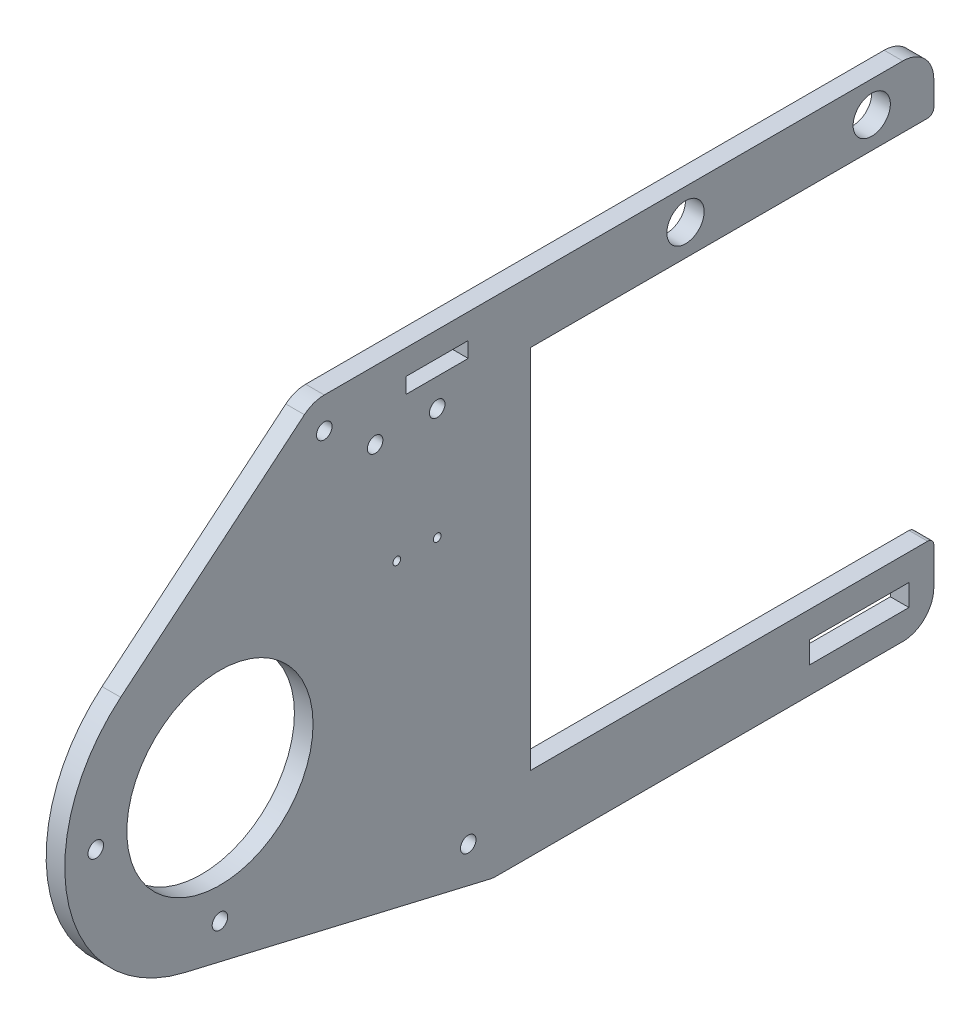
SolidWorks part; units mm, degrees
ref_plane "Front Plane" through (0, 0, 0) normal (0, 0, 1) x (1, 0, 0)
ref_plane "Top Plane" through (0, 0, 0) normal (0, 1, 0) x (1, 0, 0)
ref_plane "Right Plane" through (0, 0, 0) normal (1, 0, 0) x (0, 0, -1)
other "Configuration Table"
sketch "Sketch1" plane through (0, 0, 0) normal (1, 0, 0) x (0, 0, -1)
  line L0 (0, 5) -> (65, 5)
  line L1 (0, 0) -> (150, 0) construction
  line L2 (0, 0) -> (0, -34) construction
  line L3 (0, -34) -> (150, -34) construction
  line L4 (150, 0) -> (150, -34) construction
  line L5 (65, 5) -> (65, 15)
  line L6 (65, 15) -> (-35, 15)
  line L7 (-35, 15) -> (-65.989, -10.7815)
  line L8 (-6, -66) -> (65, -66)
  line L9 (65, -66) -> (65, -54)
  line L10 (65, -54) -> (0, -54)
  line L11 (0, -54) -> (0, 5)
  line L12 (-30, 5) -> (-10, 5) construction
  line L13 (-10, 5) -> (-10, 11) construction
  line L14 (-10, 11) -> (-30, 11) construction
  line L15 (-30, 11) -> (-30, 5) construction
  line L16 (-50, -30) -> (-50, 5) construction
  line L17 (-50, -30) -> (0, -30) construction
  line L18 (-65, 2.5) -> (-35, 2.5) construction
  line L19 (-65, 2.5) -> (-65, 202.5) construction
  line L20 (-65, 202.5) -> (-35, 202.5) construction
  line L21 (-35, 2.5) -> (-35, 202.5) construction
  line L23 (-20, 11) -> (-10, 11)
  line L24 (-6, -66) -> (-55.7094, -54.3393)
  line L25 (55, 10) -> (65, 10) construction
  line L34 (-20, 11) -> (-20, 5) construction
  line L35 (-20, -5) -> (-20, -62.7159) construction
  line L36 (45, -58.25) -> (61, -58.25)
  line L37 (45, -58.25) -> (45, -61.75)
  line L38 (-59.0397, -5) -> (0, -5) construction
  line L39 (45, -61.75) -> (61, -61.75)
  line L40 (61, -58.25) -> (61, -61.75)
  line L43 (45, -60) -> (65, -60) construction
  line L44 (-20, 11) -> (-20, 8.5)
  line L45 (-20, 8.5) -> (-10, 8.5)
  line L46 (-10, 11) -> (-10, 8.5)
  circle A0 centre (-50, -30) radius 15
  arc A1 (-65.989, -10.7815) -> (-55.7094, -54.3393) centre (-50, -30) ccw
  circle A2 centre (55, 10) radius 3
  circle A3 centre (25, 10) radius 3
  circle A4 centre (-50, -30) radius 15 construction
  circle A6 centre (-33.1921, 10) radius 1.25
  circle A7 centre (-50, -50) radius 1.25
  circle A8 centre (-70, -30) radius 1.25
  circle A9 centre (-10, -59.2554) radius 1.25
  circle A22 centre (-25, 4) radius 1.25
  circle A23 centre (-15, 4) radius 1.25
  circle A26 centre (-15, -14) radius 0.625
  circle A27 centre (-21.5, -14) radius 0.625
  point P21 (-20, 5)
  point P22 (-50, 2.5)
  point P24 (32.5, 5)
  point P37 (45, -60)
  point P42 (65, 10)
  dimension "D3" = 30
  dimension "D19" = 50
  dimension "D25" = 6
  dimension "D26" = 30
  dimension "D27" = 2.5
  dimension "D28" = 2.5
  dimension "D29" = 2.5
  dimension "D32" = 6.5
  dimension "D13" = 3.5
  dimension "D33" = 1.25
  dimension "D1" = 34
  dimension "D2" = 150
  dimension "D4" = 50
  dimension "D5" = 30
  dimension "D6" = 30
  dimension "D7" = 20
  dimension "D8" = 6
  dimension "D9" = 35
  dimension "D10" = 200
  dimension "D11" = 30
  dimension "D12" = 32.5
  dimension "D14" = 20
  dimension "D15" = 5
  dimension "D16" = 65
  dimension "D17" = 12
  dimension "D18" = 10
  dimension "D20" = 6
  dimension "D21" = 16
  dimension "D22" = 20
  dimension "D23" = 16
  dimension "D24" = 30
  dimension "D30" = 10
  dimension "D31" = 9
  dimension "D34" = 52
extrude "Boss-Extrude1" add sketch "Sketch1" along normal blind 3
fillet "Fillet1" radius 5 4 edges at (1.5, -66, 6) (1.5, -66, -65) (1.5, 15, -65) (1.5, 15, 35)
fillet "Fillet2" radius 1 2 edges at (1.5, -54, -65) (1.5, 5, -65)
